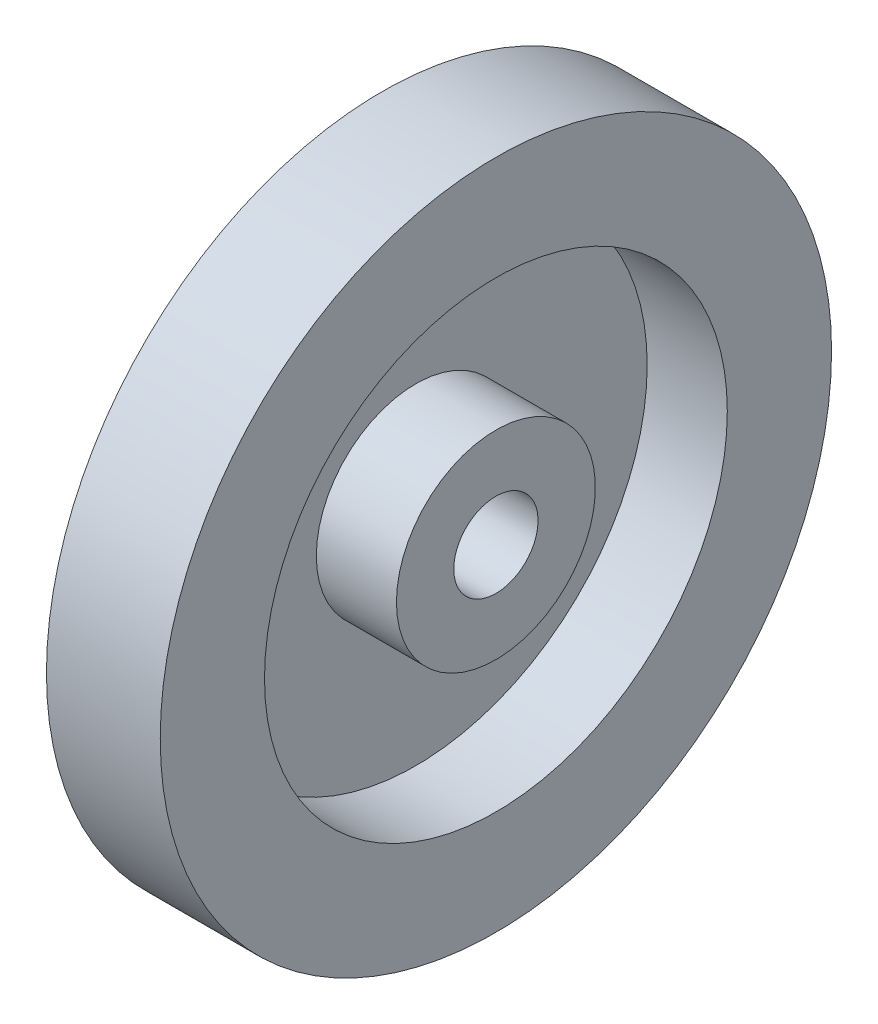
SolidWorks part; units mm, degrees
ref_plane "Front Plane" through (0, 0, 0) normal (0, 0, 1) x (1, 0, 0)
ref_plane "Top Plane" through (0, 0, 0) normal (0, 1, 0) x (1, 0, 0)
ref_plane "Right Plane" through (0, 0, 0) normal (1, 0, 0) x (0, 0, -1)
sketch "Sketch1" plane through (0, 0, 0) normal (0, 0, 1) x (1, 0, 0)
  line L0 (0, 159.3263) -> (54.0164, 159.3263)
  line L1 (54.0164, 159.3263) -> (54.0164, 109.8407)
  line L2 (54.0164, 109.8407) -> (15.9873, 109.8407)
  line L3 (15.9873, 109.8407) -> (15.9873, 47.214)
  line L4 (15.9873, 47.214) -> (54.0164, 47.214)
  line L5 (54.0164, 47.214) -> (54.0164, 20)
  line L6 (54.0164, 20) -> (0, 20)
  line L7 (0, 20) -> (0, 159.3263)
  line L8 (0, 20) -> (0, -8.8886) construction
  line L9 (0, 0) -> (37.3285, 0) construction
  dimension "D1" = 20
revolve "Revolve1" add sketch "Sketch1" angle 360 about L9
